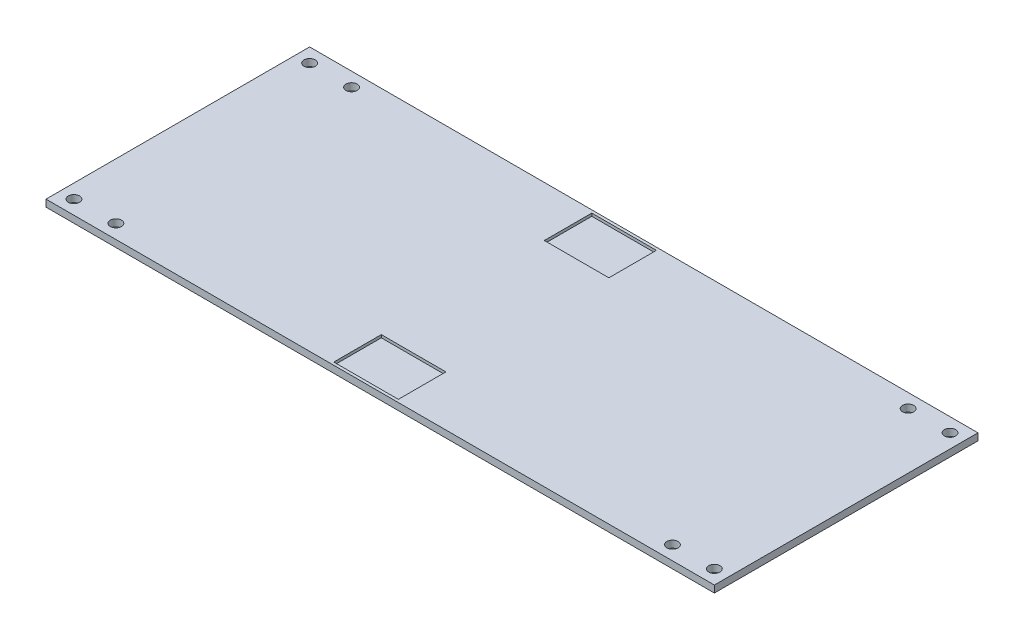
SolidWorks part; units mm, degrees
ref_plane "Plan de face" through (0, 0, 0) normal (0, 0, 1) x (1, 0, 0)
ref_plane "Plan de dessus" through (0, 0, 0) normal (0, 1, 0) x (1, 0, 0)
ref_plane "Plan de droite" through (0, 0, 0) normal (1, 0, 0) x (0, 0, -1)
sketch "Esquisse1" plane through (0, 0, 0) normal (0, 1, 0) x (1, 0, 0)
  line L0 (-72.9175, 47.0853) -> (405.2361, 47.0853)
  line L1 (-72.9175, 141.3821) -> (405.2361, 141.3821)
  line L2 (-72.9175, 141.3821) -> (-72.9175, -47.2116)
  line L3 (-72.9175, -47.2116) -> (405.2361, -47.2116)
  line L4 (405.2361, 141.3821) -> (405.2361, -47.2116)
  line L5 (-72.9175, -47.2116) -> (-62.9175, -47.2116)
  line L6 (-72.9175, -47.2116) -> (-72.9175, -37.2116)
  line L7 (-72.9175, -37.2116) -> (-62.9175, -37.2116)
  line L8 (-62.9175, -47.2116) -> (-62.9175, -37.2116)
  line L9 (-72.9175, 141.3821) -> (-62.9175, 141.3821)
  line L10 (-72.9175, 141.3821) -> (-72.9175, 131.3821)
  line L11 (-72.9175, 131.3821) -> (-62.9175, 131.3821)
  line L12 (-62.9175, 141.3821) -> (-62.9175, 131.3821)
  line L13 (405.2361, 141.3821) -> (395.2361, 141.3821)
  line L14 (405.2361, 141.3821) -> (405.2361, 131.3821)
  line L15 (405.2361, 131.3821) -> (395.2361, 131.3821)
  line L16 (395.2361, 141.3821) -> (395.2361, 131.3821)
  line L17 (405.2361, -47.2116) -> (395.2361, -47.2116)
  line L18 (405.2361, -47.2116) -> (405.2361, -37.2116)
  line L19 (405.2361, -37.2116) -> (395.2361, -37.2116)
  line L20 (395.2361, -47.2116) -> (395.2361, -37.2116)
  line L21 (166.1593, 141.3821) -> (166.1593, -47.2116)
  line L22 (-62.9175, 131.3821) -> (-32.9175, 131.3821)
  line L23 (166.1593, 47.0853) -> (200.1593, 47.0853)
  line L24 (166.1593, 47.0853) -> (166.1593, 56.9161)
  line L25 (166.1593, 56.9161) -> (200.1593, 56.9161)
  line L26 (200.1593, 47.0853) -> (200.1593, 56.9161)
  line L27 (166.1593, 56.9161) -> (132.1593, 56.9161)
  line L28 (166.1593, 56.9161) -> (166.1593, 47.0853)
  line L29 (166.1593, 47.0853) -> (132.1593, 47.0853)
  line L30 (132.1593, 56.9161) -> (132.1593, 47.0853)
  line L31 (-62.9175, -37.2116) -> (-32.9175, -37.2116)
  line L32 (395.2361, -37.2116) -> (365.2361, -37.2116)
  line L33 (395.2361, 131.3821) -> (365.2361, 131.3821)
  line L35 (132.1593, 47.0853) -> (200.1593, 47.0853)
  line L36 (132.1593, 47.0853) -> (132.1593, 39.6053)
  line L37 (132.1593, 39.6053) -> (200.1593, 39.6053)
  line L38 (200.1593, 47.0853) -> (200.1593, 39.6053)
  line L39 (132.1593, 56.9161) -> (200.1593, 56.9161)
  line L40 (132.1593, 56.9161) -> (132.1593, 102.9161)
  line L41 (132.1593, 102.9161) -> (200.1593, 102.9161)
  line L42 (200.1593, 56.9161) -> (200.1593, 102.9161)
  line L43 (132.1593, 39.6053) -> (200.1593, 39.6053)
  line L44 (132.1593, 39.6053) -> (132.1593, -6.3947)
  line L45 (132.1593, -6.3947) -> (200.1593, -6.3947)
  line L46 (200.1593, 39.6053) -> (200.1593, -6.3947)
  circle A0 centre (-62.9175, 131.3821) radius 4
  circle A1 centre (-62.9175, -37.2116) radius 4
  circle A2 centre (395.2361, -37.2116) radius 4
  circle A3 centre (395.2361, 131.3821) radius 4
  circle A4 centre (-32.9175, -37.2116) radius 4
  circle A5 centre (-32.9175, 131.3821) radius 4
  circle A6 centre (365.2361, 131.3821) radius 4
  circle A7 centre (365.2361, -37.2116) radius 4
extrude "Boss.-Extru.4" add sketch "Esquisse1" along normal blind 5
sketch "Esquisse2" plane through (0, 5, 0) normal (0, 1, 0) x (1, 0, 0)
  line L0 (-72.9175, -47.2116) -> (166.1593, -47.2116)
  line L1 (-72.9175, -47.2116) -> (405.2361, -47.2116) construction
  line L2 (166.1593, -47.2116) -> (166.1593, 141.3821)
  line L3 (-72.9175, 141.3821) -> (405.2361, 141.3821) construction
  line L4 (166.1593, -47.2116) -> (177.1593, -47.2116)
  line L5 (177.1593, -47.2116) -> (177.1593, 141.3821)
  line L6 (166.1593, 141.3821) -> (166.1593, 139.3821)
  line L7 (166.1593, 139.3821) -> (177.1593, 139.3821)
  line L8 (177.1593, -47.2116) -> (177.1593, -45.2116)
  line L9 (177.1593, -45.2116) -> (166.1593, -45.2116)
  line L10 (177.1593, -45.2116) -> (130.9593, -45.2116)
  line L11 (130.9593, -45.2116) -> (130.9593, 141.3821)
  line L12 (166.1593, 139.3821) -> (130.9593, 139.3821)
  line L13 (130.9593, -45.2116) -> (130.9593, -11.2116)
  line L14 (130.9593, -11.2116) -> (177.1593, -11.2116)
  line L15 (177.1593, 139.3821) -> (177.1593, 105.3821)
  line L16 (177.1593, 105.3821) -> (130.9593, 105.3821)
extrude "Enlèv. mat.-Extru.1" cut sketch "Esquisse2" against normal blind 2 contours L16 L2 L12 L11 | L16 L5 L7 L2 | L14 L11 L10 L2 | L14 L2 L9 L5
